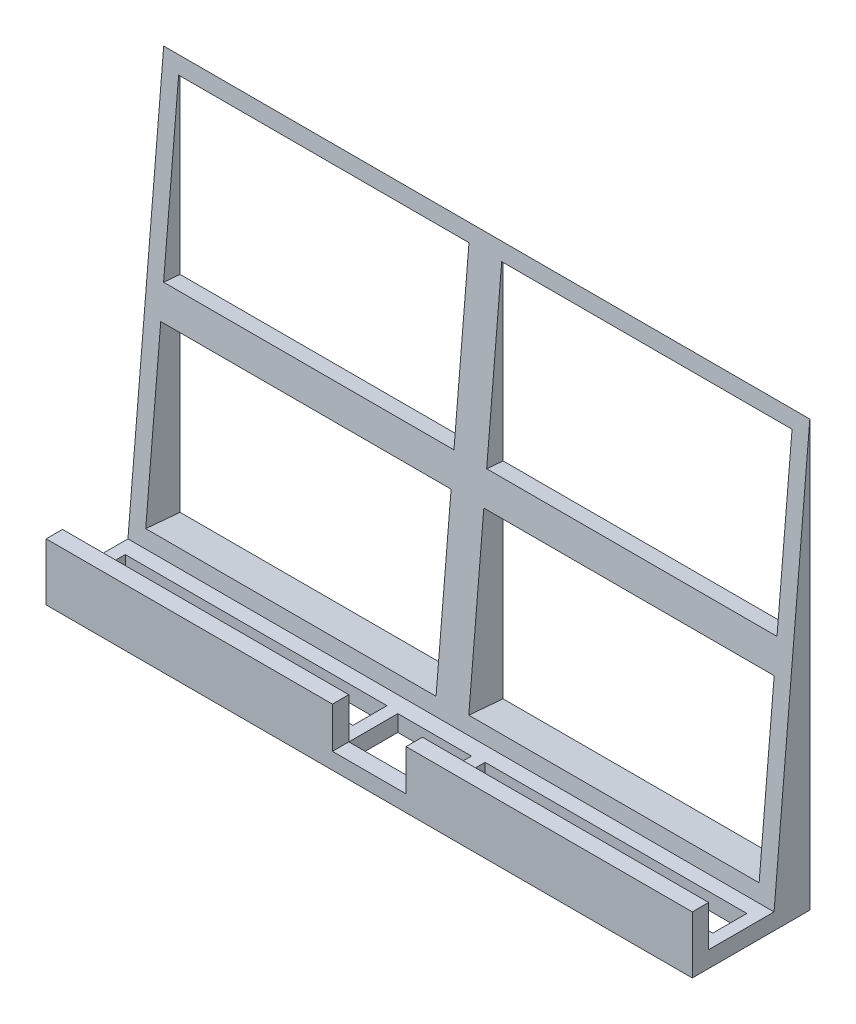
SolidWorks part; units mm, degrees
ref_plane "Alzado" through (0, 0, 0) normal (0, 0, 1) x (1, 0, 0)
ref_plane "Planta" through (0, 0, 0) normal (0, 1, 0) x (1, 0, 0)
ref_plane "Vista lateral" through (0, 0, 0) normal (1, 0, 0) x (0, 0, -1)
sketch "Croquis1" plane through (0, 0, 0) normal (0, 1, 0) x (1, 0, 0)
  line L1 (39.5, -7.185) -> (-39.5, -7.185)
  line L2 (39.5, -7.185) -> (39.5, 7.185)
  line L3 (39.5, 7.185) -> (-39.5, 7.185)
  line L4 (-39.5, -7.185) -> (-39.5, 7.185)
  line L5 (39.5, -7.185) -> (-39.5, 7.185) construction
  line L6 (39.5, 7.185) -> (-39.5, -7.185) construction
  point P0 (0, 0)
  dimension "D1" = 14.37
  dimension "D2" = 79
extrude "Saliente-Extruir1" add sketch "Croquis1" along normal blind 2
sketch "Croquis2" plane through (39.5, 0, 0) normal (1, 0, 0) x (0, 0, -1)
  line L0 (2.8106, 2) -> (7.185, 52)
  line L1 (-7.185, 2) -> (7.185, 2) construction
  line L2 (7.185, 52) -> (7.185, 2)
  line L3 (7.185, 2) -> (7.185, 0) construction
  line L4 (7.185, 2) -> (2.8106, 2)
  dimension "D1" = 95
  dimension "D2" = 50
extrude "Saliente-Extruir2" add sketch "Croquis2" against normal up to surface (79 mm away) up to face at (-39.5, 1, 0)
sketch "Croquis4" plane through (0, 2, 0) normal (0, 1, 0) x (1, 0, 0)
  line L1 (-39.5, -7.185) -> (-4.5, -7.185)
  line L2 (-39.5, -7.185) -> (-39.5, -5.185)
  line L3 (-39.5, -5.185) -> (-4.5, -5.185)
  line L4 (-4.5, -7.185) -> (-4.5, -5.185)
  line L5 (-39.5, -7.185) -> (-4.5, -5.185) construction
  line L6 (-39.5, -5.185) -> (-4.5, -7.185) construction
  point P4 (-22, -6.185)
  dimension "D1" = 35
  dimension "D2" = 2
extrude "Saliente-Extruir3" add sketch "Croquis4" along normal blind 5
mirror "Simetría1" about plane through (0, 0, 0) normal (1, 0, 0) of "Saliente-Extruir3"
sketch "Croquis5" plane through (0, 2, 0) normal (0, 1, 0) x (1, 0, 0)
  line L0 (-39.5, 2.8106) -> (39.5, 2.8106) construction
  line L1 (-4.5, 2.8106) -> (4.5, 2.8106)
  line L2 (-4.5, 2.8106) -> (-4.5, -7.185)
  line L3 (-4.5, -7.185) -> (4.5, -7.185)
  line L4 (4.5, 2.8106) -> (4.5, -7.185)
  line L5 (-4.5, 2.8106) -> (4.5, -7.185) construction
  line L6 (-4.5, -7.185) -> (4.5, 2.8106) construction
  line L7 (-4.5, -7.185) -> (4.5, -7.185) construction
  point P4 (0, -2.1872)
  point P5 (0, 0)
  point P8 (0, 0)
  dimension "D1" = 0
  dimension "D2" = 0
extrude "Cortar-Extruir1" cut sketch "Croquis5" against normal up to next
sketch "Croquis6" plane through (0, -0.2288, -2.6156) normal (0, 0.0872, 0.9962) x (1, 0, 0)
  line L0 (0, 52.4283) -> (0, 2.2373) construction
  line L1 (-39.5, 52.4283) -> (39.5, 52.4283) construction
  line L2 (4.5, 2.2373) -> (-4.5, 2.2373) construction
  line L3 (-39.5, 27.3328) -> (39.5, 27.3328) construction
  line L4 (-37.5, 50.4283) -> (-2, 50.4283)
  line L5 (-37.5, 50.4283) -> (-37.5, 29.3328)
  line L6 (-37.5, 29.3328) -> (-2, 29.3328)
  line L7 (-2, 50.4283) -> (-2, 29.3328)
  line L8 (-37.5, 50.4283) -> (-2, 29.3328) construction
  line L9 (-37.5, 29.3328) -> (-2, 50.4283) construction
  line L10 (-39.5, 2.2373) -> (-39.5, 52.4283) construction
  line L11 (39.5, 52.4283) -> (39.5, 2.2373) construction
  line L12 (37.5, 29.3328) -> (2, 29.3328)
  line L13 (2, 50.4283) -> (2, 29.3328)
  line L14 (37.5, 50.4283) -> (2, 50.4283)
  line L15 (37.5, 50.4283) -> (37.5, 29.3328)
  line L16 (37.5, 4.2373) -> (37.5, 25.3328)
  line L17 (37.5, 4.2373) -> (2, 4.2373)
  line L18 (2, 4.2373) -> (2, 25.3328)
  line L19 (37.5, 25.3328) -> (2, 25.3328)
  line L20 (-37.5, 25.3328) -> (-2, 25.3328)
  line L21 (-2, 4.2373) -> (-2, 25.3328)
  line L22 (-37.5, 4.2373) -> (-2, 4.2373)
  line L23 (-37.5, 4.2373) -> (-37.5, 25.3328)
  point P10 (-19.75, 39.8806)
  dimension "D1" = 2
  dimension "D2" = 2
  dimension "D3" = 2
  dimension "D4" = 2
extrude "Cortar-Extruir2" cut sketch "Croquis6" against normal up to next
sketch "Croquis7" plane through (0, 2, 0) normal (0, 1, 0) x (1, 0, 0)
  line L0 (4.5, -5.185) -> (4.5, 2.8106) construction
  line L1 (6, 0.9849) -> (38, 0.9849)
  line L2 (6, 0.9849) -> (6, -3.185)
  line L3 (6, -3.185) -> (38, -3.185)
  line L4 (38, 0.9849) -> (38, -3.185)
  line L5 (6, 0.9849) -> (38, -3.185) construction
  line L6 (6, -3.185) -> (38, 0.9849) construction
  line L7 (4.5, -5.185) -> (39.5, -5.185) construction
  line L8 (2, 2.9849) -> (37.5, 2.9849) construction
  line L9 (39.5, -5.185) -> (39.5, 2.8106) construction
  point P4 (22, -1.1001)
  dimension "D1" = 1.5
  dimension "D2" = 2
  dimension "D3" = 2
  dimension "D4" = 1.5
extrude "Cortar-Extruir3" cut sketch "Croquis7" against normal up to next
mirror "Simetría4" about plane through (0, 0, 0) normal (1, 0, 0) of "Cortar-Extruir3"
sketch "Croquis8" plane through (-4.5, 0, 0) normal (1, 0, 0) x (0, 0, -1)
  line L1 (-5.185, 2) -> (-7.185, 2)
  line L2 (-5.185, 2) -> (-5.185, 0)
  line L3 (-5.185, 0) -> (-7.185, 0)
  line L4 (-7.185, 2) -> (-7.185, 0)
  line L5 (-5.185, 2) -> (-7.185, 0) construction
  line L6 (-5.185, 0) -> (-7.185, 2) construction
  point P4 (-6.185, 1)
extrude "Saliente-Extruir4" add sketch "Croquis8" along normal up to surface (9 mm away)
sketch "Croquis11" plane through (-4.5, 0, 0) normal (1, 0, 0) x (0, 0, -1)
  line L0 (2.8106, 2) -> (-5.185, 2) construction
  line L1 (2.8106, 2) -> (0.8106, 2)
  line L2 (2.8106, 2) -> (2.8106, 0)
  line L3 (2.8106, 0) -> (0.8106, 0)
  line L4 (0.8106, 2) -> (0.8106, 0)
  line L5 (2.8106, 2) -> (0.8106, 0) construction
  line L6 (2.8106, 0) -> (0.8106, 2) construction
  line L7 (-5.185, 0) -> (2.8106, 0) construction
  point P4 (1.8106, 1)
  dimension "D1" = 2
extrude "Saliente-Extruir5" add sketch "Croquis11" along normal up to surface (9 mm away)
